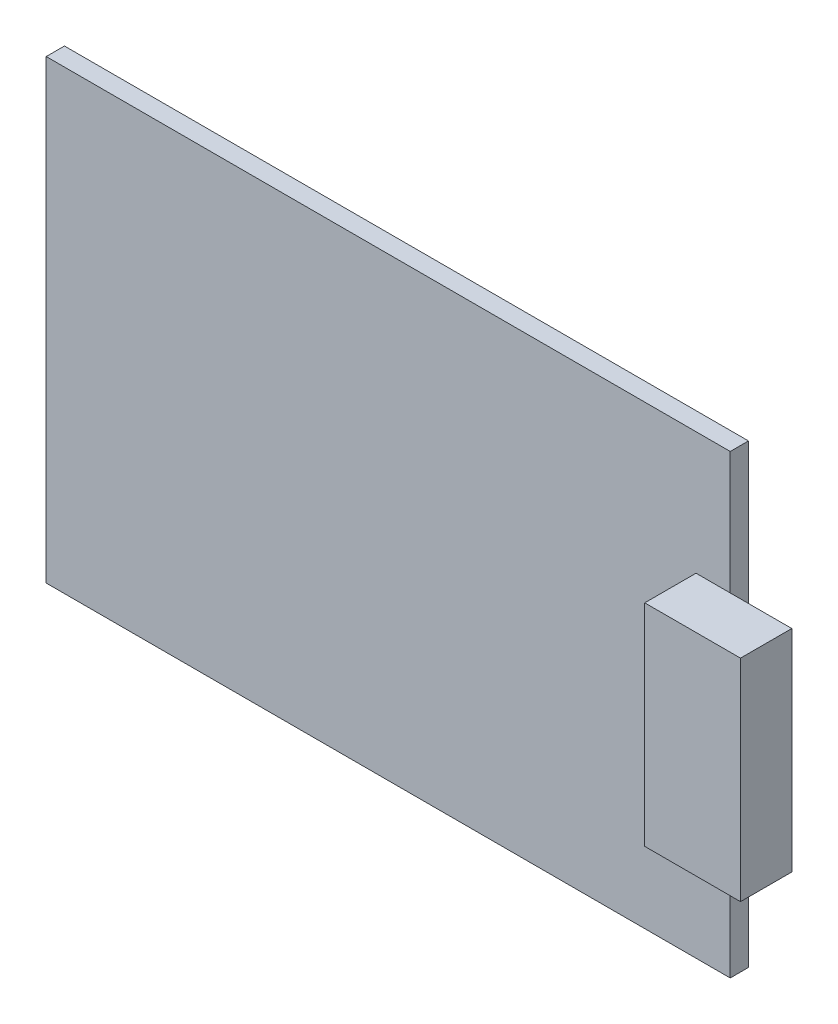
SolidWorks part; units mm, degrees
ref_plane "Front Plane" through (0, 0, 0) normal (1, 0, 0) x (0, 1, 0)
ref_plane "Top Plane" through (0, 0, 0) normal (0, 0, 1) x (0, 1, 0)
ref_plane "Right Plane" through (0, 0, 0) normal (0, 1, 0) x (-1, 0, 0)
sketch "Sketch1" plane through (0, 0, 0) normal (0, 0, 1) x (0, 1, 0)
  line L1 (20, -30) -> (-20, -30)
  line L2 (20, -30) -> (20, 30)
  line L3 (20, 30) -> (-20, 30)
  line L4 (-20, -30) -> (-20, 30)
  line L5 (20, -30) -> (-20, 30) construction
  line L6 (20, 30) -> (-20, -30) construction
  point P0 (0, 0)
  dimension "D1" = 40
  dimension "D2" = 60
extrude "Boss-Extrude1" add sketch "Sketch1" along normal blind 1.6
sketch "Sketch2" plane through (30, 0, 0) normal (1, 0, 0) x (0, 1, 0)
  line L0 (-20, 1.6) -> (20, 1.6) construction
  line L1 (-9.25, 1.6) -> (9.25, 1.6)
  line L2 (-9.25, 1.6) -> (-9.25, 6.1)
  line L3 (-9.25, 6.1) -> (9.25, 6.1)
  line L4 (9.25, 1.6) -> (9.25, 6.1)
  point P6 (0, 1.6)
  dimension "D1" = 4.5
  dimension "D2" = 18.5
extrude "Boss-Extrude2" add sketch "Sketch2" along normal blind 5.4 and the other way blind 3
